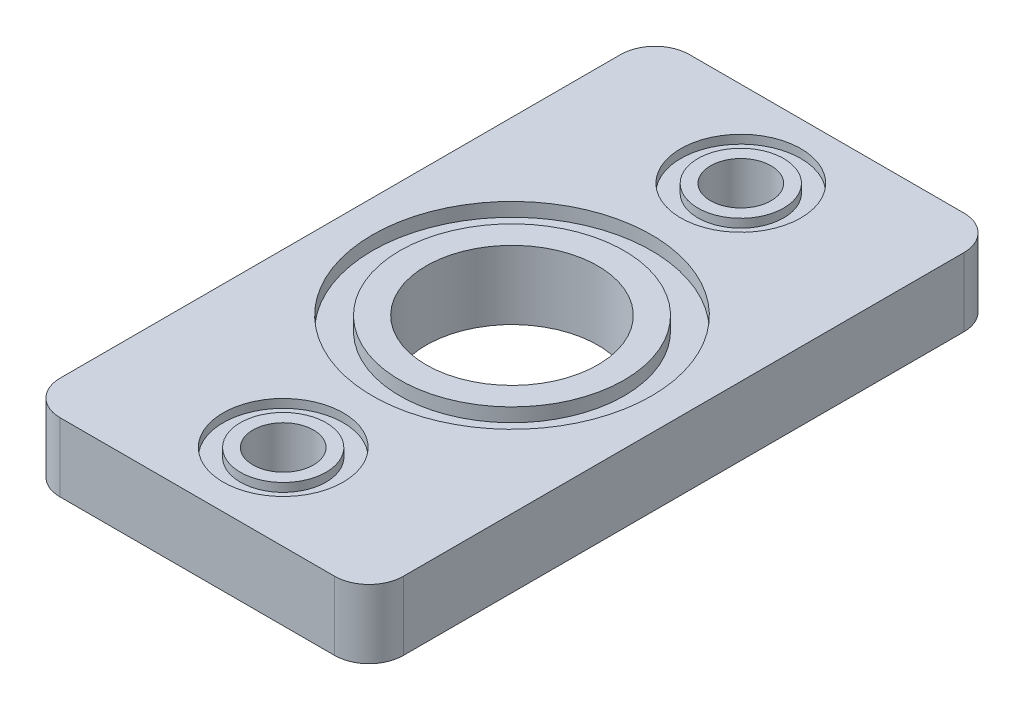
SolidWorks part; units mm, degrees
material "PVC rigide"
ref_plane "Plan de face" through (0, 0, 0) normal (0, 0, 1) x (1, 0, 0)
ref_plane "Plan de dessus" through (0, 0, 0) normal (0, 1, 0) x (1, 0, 0)
ref_plane "Plan de droite" through (0, 0, 0) normal (1, 0, 0) x (0, 0, -1)
sketch "Esquisse1" plane through (0, 0, 0) normal (0, 1, 0) x (1, 0, 0)
  line L1 (15, 27.5) -> (-15, 27.5)
  line L2 (15, 27.5) -> (15, -27.5)
  line L3 (15, -27.5) -> (-15, -27.5)
  line L4 (-15, 27.5) -> (-15, -27.5)
  line L5 (15, 27.5) -> (-15, -27.5) construction
  line L6 (15, -27.5) -> (-15, 27.5) construction
  point P0 (0, 0)
  dimension "D1" = 30
  dimension "D2" = 55
extrude "Plaque Plexi" add sketch "Esquisse1" along normal blind 6
sketch "Esquisse5" plane through (0, 6, 0) normal (0, 1, 0) x (1, 0, 0)
  circle A0 centre (0, 0) radius 7.5
  dimension "D1" = 15
extrude "Passage Jauge Laiton" cut sketch "Esquisse5" against normal up to next
sketch "Esquisse6" plane through (0, 6, 0) normal (0, 1, 0) x (1, 0, 0)
  line L8 (15, 27.5) -> (-15, 27.5) construction
  line L9 (-3.3, 0) -> (3.3, 0) construction
  circle A1 centre (0, 20) radius 2.65
  circle A7 centre (0, -20) radius 2.65
  point P1 (0, 27.5)
  dimension "D1" = 5.3
  dimension "D3" = 7.5
extrude "Passage écrou M5" cut sketch "Esquisse6" against normal up to next
sketch "Esquisse2" plane through (0, 6, 0) normal (0, 1, 0) x (1, 0, 0)
  circle A0 centre (0, 0) radius 11
  dimension "D1" = 22
extrude "Gorge_Joint_central" cut sketch "Esquisse2" against normal blind 1.2 thin thin type mid plane wall 2.4
shell "Coque2" [suppressed] thickness 10
sketch "Esquisse7" plane through (0, 6, 0) normal (0, 1, 0) x (1, 0, 0)
  circle A0 centre (0, -20) radius 4.5
  circle A1 centre (0, 20) radius 4.5
  dimension "D1" = 9
extrude "Enlèv. de mat.-Extru.-Mince2" cut sketch "Esquisse7" against normal blind 0.75 thin thin type mid plane wall 1.5
fillet "Congé1" radius 3 4 edges at (15, 3, -27.5) (-15, 3, -27.5) (-15, 3, 27.5) (15, 3, 27.5)
